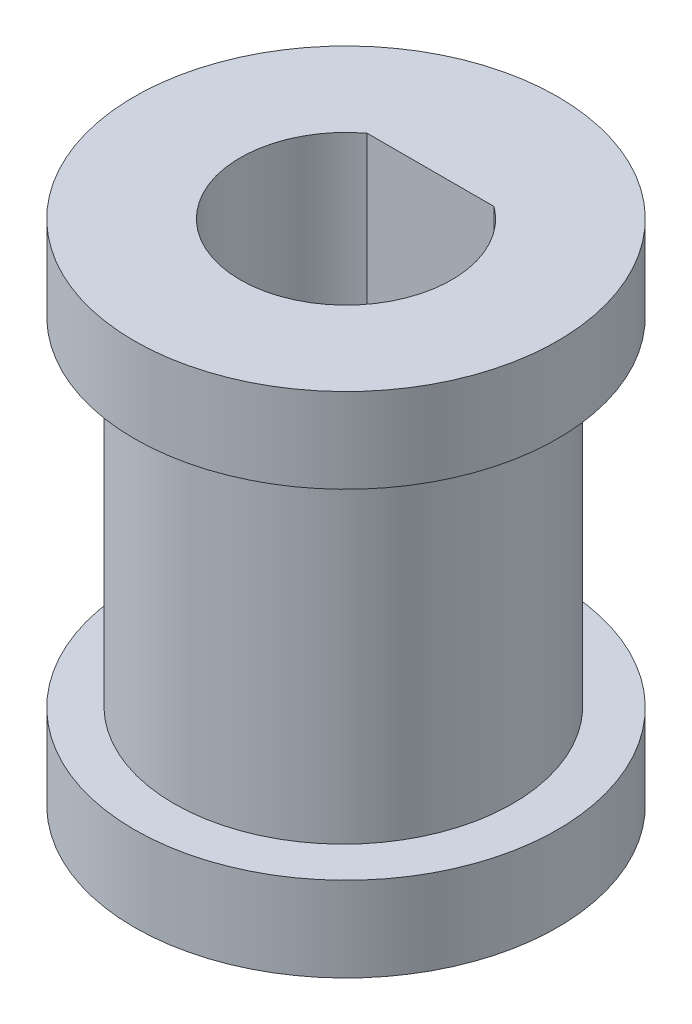
SolidWorks part; units mm, degrees
ref_plane "前视基准面" through (0, 0, 0) normal (0, 0, 1) x (1, 0, 0)
ref_plane "上视基准面" through (0, 0, 0) normal (0, 1, 0) x (1, 0, 0)
ref_plane "右视基准面" through (0, 0, 0) normal (1, 0, 0) x (0, 0, -1)
sketch "草图1" plane through (0, 0, 0) normal (0, 1, 0) x (1, 0, 0)
  line L0 (-1.5, 2) -> (1.5, 2)
  line L1 (-55, 0) -> (55, 0) construction
  circle A0 centre (0, 0) radius 2.5
  circle A1 centre (-0.063, 0) radius 4
  dimension "D1" = 5
  dimension "D3" = 8
  dimension "D2" = 3
extrude "凸台-拉伸1" add sketch "草图1" along normal blind 10 contours L0 A0 | A1 A0 L0
sketch "草图2" plane through (0, 0, 0) normal (0, 1, 0) x (1, 0, 0)
  line L0 (-1.5, 2) -> (1.5, 2) construction
  line L1 (-1.5, 2) -> (1.5, 2)
  circle A0 centre (0, 0) radius 5
  arc A1 (-1.5, 2) -> (1.5, 2) centre (0, 0) ccw construction
  arc A2 (-1.5, 2) -> (1.5, 2) centre (0, 0) ccw
  dimension "D1" = 10
extrude "凸台-拉伸3" add sketch "草图2" along normal blind 2
sketch "草图4" plane through (0, 10, 0) normal (0, 1, 0) x (1, 0, 0)
  line L0 (-1.5, 2) -> (1.5, 2) construction
  line L1 (-1.5, 2) -> (1.5, 2)
  circle A0 centre (0, 0) radius 5
  arc A1 (-1.5, 2) -> (1.5, 2) centre (0, 0) ccw construction
  arc A2 (-1.5, 2) -> (1.5, 2) centre (0, 0) ccw
extrude "凸台-拉伸4" add sketch "草图4" along normal blind 2
